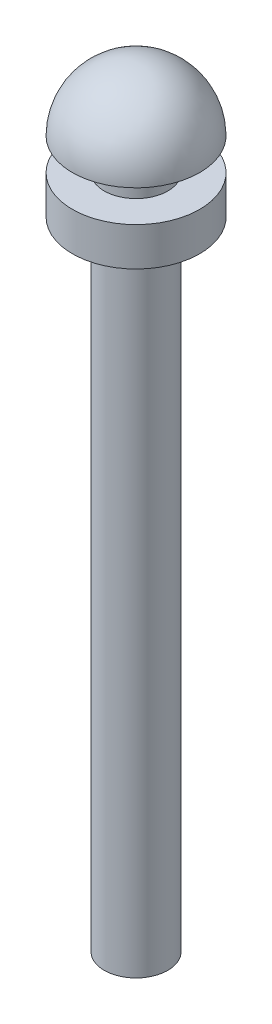
SolidWorks part; units mm, degrees
ref_plane "Front Plane" through (0, 0, 0) normal (0, 0, 1) x (1, 0, 0)
ref_plane "Top Plane" through (0, 0, 0) normal (0, 1, 0) x (1, 0, 0)
ref_plane "Right Plane" through (0, 0, 0) normal (1, 0, 0) x (0, 0, -1)
sketch "Sketch1" plane through (0, 0, 0) normal (0, 0, 1) x (1, 0, 0)
  line L0 (0, 0) -> (1, 0)
  line L1 (1, 0) -> (1, 20)
  line L2 (1, 20) -> (2, 20)
  line L3 (2, 20) -> (2, 21.2093)
  line L4 (2, 21.2093) -> (1, 21.2093)
  line L5 (1, 21.2093) -> (1, 22.2093)
  line L6 (1, 22.2093) -> (2, 22.2093)
  line L7 (0, 0) -> (0, 24.2093)
  line L8 (0, 0) -> (0, 39.8193) construction
  arc A0 (2, 22.2093) -> (0, 24.2093) centre (0, 22.2093) ccw
  dimension "D1" = 1
  dimension "D2" = 20
  dimension "D3" = 1
  dimension "D4" = 1.2093
  dimension "D5" = 1
  dimension "D6" = 1
  dimension "D7" = 1
  dimension "D8" = 0
revolve "Screw Revolve" add sketch "Sketch1" angle 360 about L8
